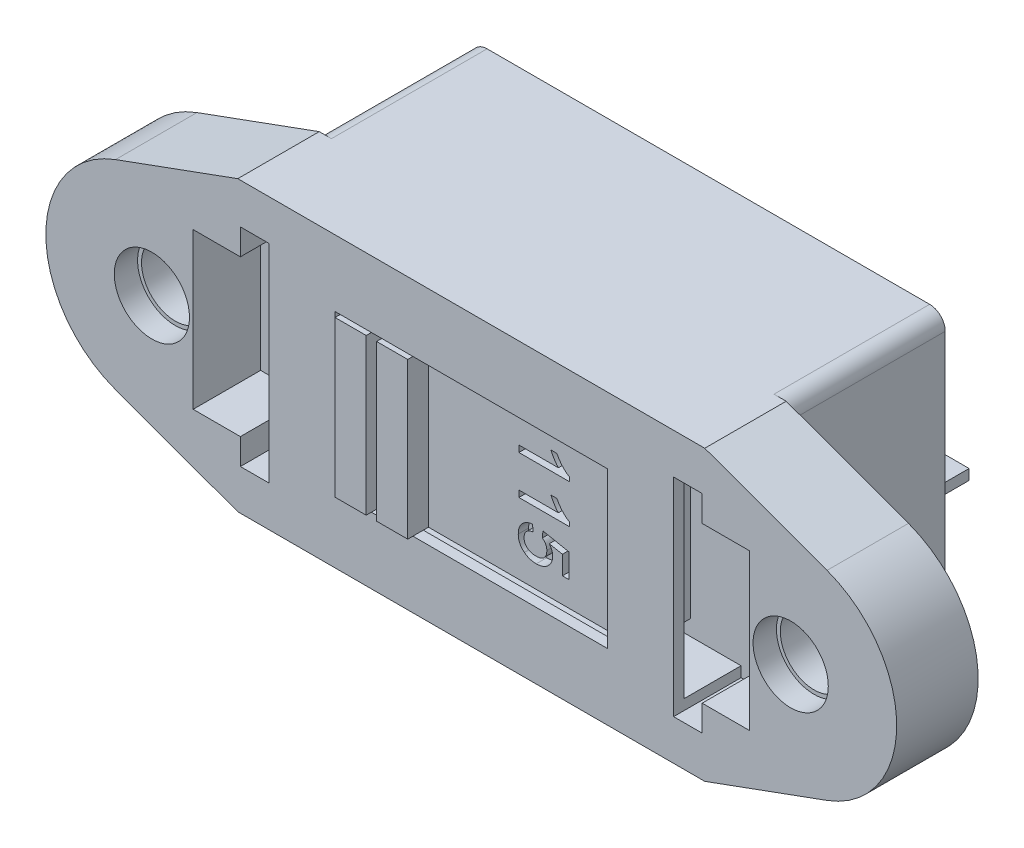
SolidWorks part; units mm, degrees
material "PW50:30:C1:0:1:2:Re:16:"
ref_plane "Plane1" through (0, 0, 0) normal (0, 0, 1) x (1, 0, 0)
ref_plane "Plane2" through (0, 0, 0) normal (0, 1, 0) x (1, 0, 0)
ref_plane "Plane3" through (0, 0, 0) normal (1, 0, 0) x (0, 0, -1)
sketch "Sketch1" plane through (0, 0, 0) normal (0, 0, 1) x (1, 0, 0)
  line L0 (-11.43, 7.0612) -> (11.43, 7.0612)
  line L2 (11.43, -7.0612) -> (-11.43, -7.0612)
  line L4 (0, 0) -> (0, 35.56) construction
  line L5 (0, 0) -> (86.36, 0) construction
  line L6 (11.43, 7.0612) -> (17.4162, 4.8768)
  line L7 (-11.43, 7.0612) -> (-17.4162, 4.8768)
  line L8 (17.4162, -4.8768) -> (11.43, -7.0612)
  line L9 (-17.4162, -4.8768) -> (-11.43, -7.0612)
  arc A0 (17.4162, -4.8768) -> (17.4162, 4.8768) centre (15.6366, 0) ccw
  arc A1 (-17.4162, -4.8768) -> (-17.4162, 4.8768) centre (-15.6366, 0) cw
  circle A2 centre (-15.6366, 0) radius 1.651
  circle A3 centre (15.6366, 0) radius 1.651
  dimension "D2" = 41.656
  dimension "D4" = 5.1914
  dimension "D5" = 3.302
  dimension "D1" = 14.1224
  dimension "D3" = 22.86
extrude "Base-Extrude" add sketch "Sketch1" along normal blind 3.9878
sketch "Sketch2" plane through (0, 0, 3.9878) normal (0, 0, 1) x (1, 0, 0)
  line L0 (0, 0) -> (0, 12.5534) construction
  circle A0 centre (15.6366, 0) radius 1.8415
  circle A1 centre (-15.6366, 0) radius 1.8415
  arc A2 (17.4162, -4.8768) -> (17.4162, 4.8768) centre (15.6366, 0) ccw construction
  dimension "D1" = 3.683
extrude "Cut-Extrude1" cut sketch "Sketch2" against normal blind 1.143
sketch "Sketch3" plane through (0, 0, 3.9878) normal (0, 0, 1) x (1, 0, 0)
  line L0 (0, 0) -> (0, 14.0337) construction
  line L1 (-9.906, -5.08) -> (-9.906, 5.08)
  line L2 (-11.303, -3.81) -> (-13.6144, -3.81)
  line L3 (-11.303, 3.81) -> (-11.303, 5.08)
  line L4 (-13.6144, 3.81) -> (-11.303, 3.81)
  line L5 (11.303, 5.08) -> (9.906, 5.08)
  line L6 (13.6144, 3.81) -> (13.6144, -3.81)
  line L7 (9.906, -5.08) -> (11.303, -5.08)
  line L8 (11.303, -5.08) -> (11.303, -3.81)
  line L9 (-11.303, -5.08) -> (-11.303, -3.81)
  line L10 (15.5437, 0) -> (22.6494, 0) construction
  line L11 (-9.906, -5.08) -> (-11.303, -5.08)
  line L12 (-13.6144, 3.81) -> (-13.6144, -3.81)
  line L13 (13.6144, 3.81) -> (11.303, 3.81)
  line L14 (11.303, 3.81) -> (11.303, 5.08)
  line L15 (11.303, -3.81) -> (13.6144, -3.81)
  line L16 (9.906, -5.08) -> (9.906, 5.08)
  line L17 (-11.303, 5.08) -> (-9.906, 5.08)
  line L18 (-6.6675, 3.81) -> (6.6675, 3.81)
  line L19 (-6.6675, 3.81) -> (-6.6675, -3.81)
  line L20 (6.6675, -3.81) -> (-6.6675, -3.81)
  line L21 (6.6675, -3.81) -> (6.6675, 3.81)
  dimension "D1" = 3.7084
  dimension "D2" = 1.397
  dimension "D3" = 7.62
  dimension "D4" = 10.16
  dimension "D5" = 9.906
  dimension "D6" = 13.335
extrude "Cut-Extrude2" cut sketch "Sketch3" against normal blind 3.302
sketch "Sketch4" plane through (9.906, 0, 0) normal (1, 0, 0) x (0, 0, -1)
  line L0 (-0.6858, -5.08) -> (-0.6858, 5.08) construction
  line L1 (-0.6858, -4.572) -> (-0.6858, 4.572)
  line L4 (-1.1938, 4.572) -> (-3.4798, 4.572)
  line L5 (-3.4798, 4.572) -> (-3.4798, -4.572)
  line L6 (-3.4798, -4.572) -> (-1.1938, -4.572)
  line L7 (-1.1938, -4.572) -> (-1.1938, 4.572)
  line L8 (-0.6858, 4.572) -> (-3.4798, 4.572)
  line L9 (-3.4798, 4.572) -> (-3.4798, -4.572)
  line L10 (-3.4798, -4.572) -> (-0.6858, -4.572)
  dimension "D1" = 0.508
extrude "Cut-Extrude3" cut sketch "Sketch4" against normal up to surface (19.812 mm away)
sketch "Sketch5" plane through (0, 0, 0) normal (0, 0, -1) x (-1, 0, 0)
  line L0 (-11.43, -7.0612) -> (11.43, -7.0612) construction
  line L1 (11.43, 7.0612) -> (-11.43, 7.0612) construction
  line L2 (-10.8331, -7.0612) -> (10.8331, -7.0612)
  line L3 (10.8331, 7.0612) -> (-10.8331, 7.0612)
  line L4 (0, 0) -> (0, 14.2114) construction
  line L5 (11.5951, 6.2992) -> (11.5951, -6.2992)
  line L6 (-11.5951, 6.2992) -> (-11.5951, -6.2992)
  arc A0 (-11.5951, -6.2992) -> (-10.8331, -7.0612) centre (-10.8331, -6.2992) ccw
  arc A1 (11.5951, -6.2992) -> (10.8331, -7.0612) centre (10.8331, -6.2992) cw
  arc A2 (11.5951, 6.2992) -> (10.8331, 7.0612) centre (10.8331, 6.2992) ccw
  arc A3 (-11.5951, 6.2992) -> (-10.8331, 7.0612) centre (-10.8331, 6.2992) cw
  dimension "D2" = 0.762
  dimension "D1" = 23.1902
extrude "Boss-Extrude1" add sketch "Sketch5" along normal blind 7.62
sketch "Sketch6" plane through (0, 0, -7.62) normal (0, 0, -1) x (-1, 0, 0)
  line L4 (-10.8331, -6.2992) -> (10.8331, -6.2992)
  line L5 (10.8331, -6.2992) -> (10.8331, 6.2992)
  line L6 (10.8331, 6.2992) -> (-10.8331, 6.2992)
  line L7 (-10.8331, 6.2992) -> (-10.8331, -6.2992)
  line L8 (-10.8331, -6.2992) -> (10.8331, -6.2992)
  line L9 (10.8331, -6.2992) -> (10.8331, 6.2992)
  line L10 (10.8331, 6.2992) -> (-10.8331, 6.2992)
  line L11 (-10.8331, 6.2992) -> (-10.8331, -6.2992)
  dimension "D1" = 0.762
extrude "Cut-Extrude4" cut sketch "Sketch6" against normal blind 1.524
sketch "Sketch7" plane through (0, 0, 0.6858) normal (0, 0, -1) x (-1, 0, 0)
  line L0 (9.906, -5.08) -> (9.906, 5.08) construction
  line L1 (-6.6675, -3.81) -> (6.6675, -3.81) construction
  line L2 (6.6675, 3.81) -> (-6.6675, 3.81) construction
  line L3 (9.906, -3.81) -> (9.906, 3.81)
  line L4 (-7.4295, -3.81) -> (9.906, -3.81)
  line L5 (9.906, 3.81) -> (-7.4295, 3.81)
  line L7 (-7.4295, -3.81) -> (-7.4295, 3.81)
  line L8 (-7.4295, -3.81) -> (-7.4295, 3.81)
  dimension "D1" = 0.762
extrude "Boss-Extrude7" add sketch "Sketch7" against normal offset from surface (2.54 mm away) 0.762
sketch "Sketch8" plane through (0, 0, 3.2258) normal (0, 0, 1) x (1, 0, 0)
  line L0 (6.6675, -3.81) -> (-6.6675, -3.81) construction
  line L1 (-6.4135, 3.81) -> (-6.4135, -3.81)
  line L2 (-6.4135, 3.81) -> (-6.4135, -3.81)
  line L3 (-4.8895, 3.81) -> (-4.8895, -3.81)
  line L4 (-4.8895, 3.81) -> (-4.8895, -3.81)
  line L5 (-4.3815, 3.81) -> (-4.3815, -3.81)
  line L6 (-4.3815, 3.81) -> (-4.3815, -3.81)
  line L7 (-2.8575, 3.81) -> (-2.8575, -3.81)
  line L8 (-2.8575, 3.81) -> (-2.8575, -3.81)
  line L9 (-6.6675, 3.81) -> (6.6675, 3.81) construction
  line L10 (-2.8575, -3.81) -> (-4.3815, -3.81)
  line L11 (-6.4135, 3.81) -> (-4.8895, 3.81)
  line L12 (-4.8895, -3.81) -> (-6.4135, -3.81)
  line L13 (-4.3815, 3.81) -> (-2.8575, 3.81)
  dimension "D1" = 0.254
  dimension "D2" = 1.778
  dimension "D3" = 2.286
  dimension "D4" = 3.81
extrude "Boss-Extrude8" add sketch "Sketch8" along normal blind 1.016
sketch "Sketch10" plane through (3.168, 12.0955, 3.2258) normal (0, 0, 1) x (0, -1, 0)
  text T0 "115" font "Century Gothic" height 2.54
extrude "Cut-Extrude5" cut sketch "Sketch10" against normal blind 0.508
sketch "Sketch11" plane through (0, 0, -6.096) normal (0, 0, -1) x (-1, 0, 0)
  line L0 (0, 0) -> (0, 11.7244) construction
  line L1 (-7.9375, -3.7592) -> (-4.1275, -3.7592)
  line L2 (-7.9375, -3.7592) -> (-7.9375, -4.2672)
  line L3 (-4.1275, -4.2672) -> (-7.9375, -4.2672)
  line L4 (-4.1275, -4.2672) -> (-4.1275, -3.7592)
  line L5 (7.9375, -3.7592) -> (4.1275, -3.7592)
  line L6 (7.9375, -3.7592) -> (7.9375, -4.2672)
  line L7 (4.1275, -4.2672) -> (7.9375, -4.2672)
  line L8 (4.1275, -4.2672) -> (4.1275, -3.7592)
  line L9 (-10.8331, -6.2992) -> (10.8331, -6.2992) construction
  dimension "D1" = 3.81
  dimension "D2" = 0.508
  dimension "D3" = 2.032
  dimension "D4" = 15.875
extrude "Boss-Extrude9" add sketch "Sketch11" along normal blind 6.35
sketch "Sketch12" plane through (0, -3.7592, 0) normal (0, 1, 0) x (-1, 0, 0)
  line L0 (-7.9375, -12.446) -> (-7.9375, -6.096) construction
  line L1 (-6.0325, -12.446) -> (-6.0325, -14.0613) construction
  line L2 (-7.9375, -12.446) -> (-4.1275, -12.446) construction
  line L3 (-4.1275, -12.446) -> (-4.1275, -6.096) construction
  line L4 (-4.1275, -11.049) -> (-4.1275, -9.779)
  line L5 (-7.9375, -11.049) -> (-7.9375, -9.779)
  line L6 (0, 0) -> (0, -17.0486) construction
  line L7 (7.9375, -11.049) -> (7.9375, -9.779)
  line L8 (4.1275, -11.049) -> (4.1275, -9.779)
  arc A0 (-7.9375, -11.049) -> (-7.9375, -9.779) centre (-7.9375, -10.414) ccw
  arc A1 (-4.1275, -11.049) -> (-4.1275, -9.779) centre (-4.1275, -10.414) cw
  arc A2 (4.1275, -11.049) -> (4.1275, -9.779) centre (4.1275, -10.414) ccw
  arc A3 (7.9375, -11.049) -> (7.9375, -9.779) centre (7.9375, -10.414) cw
  dimension "D1" = 0.635
  dimension "D2" = 2.032
extrude "Cut-Extrude6" cut sketch "Sketch12" against normal blind 1.27
